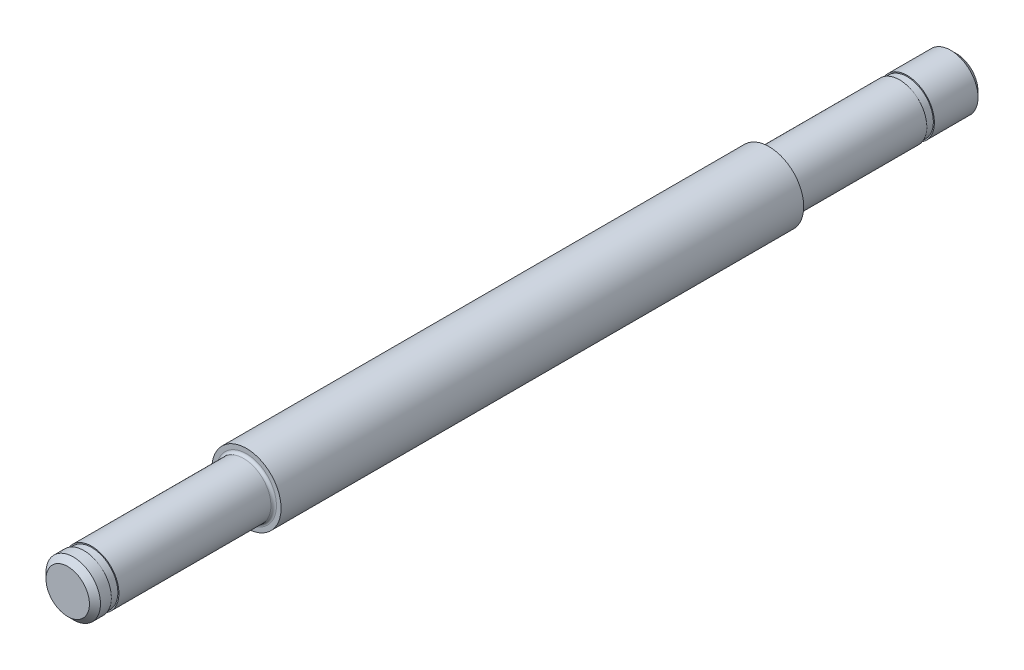
SolidWorks part; units mm, degrees
ref_plane "Front Plane" through (0, 0, 0) normal (0, 0, 1) x (1, 0, 0)
ref_plane "Top Plane" through (0, 0, 0) normal (0, 1, 0) x (1, 0, 0)
ref_plane "Right Plane" through (0, 0, 0) normal (1, 0, 0) x (0, 0, -1)
sketch "Sketch1" plane through (0, 0, 0) normal (0, 0, 1) x (1, 0, 0)
  circle A0 centre (0, 0) radius 2.5
  dimension "D1" = 5
extrude "Boss-Extrude1" add sketch "Sketch1" along normal mid plane 81.534
ref_axis "Axis1" through (0, 0, 40.767) along (0, 0, -1)
sketch "Sketch2" plane through (0, 0, 0) normal (1, 0, 0) x (0, 0, -1)
  line L0 (40.767, 2.5) -> (-40.767, 2.5) construction
  line L1 (-39.2646, 2.5) -> (-38.5646, 2.5)
  line L2 (-39.2646, 2.5) -> (-39.2646, 2.4)
  line L3 (-39.2646, 2.4) -> (-38.5646, 2.4)
  line L4 (-38.5646, 2.5) -> (-38.5646, 2.4)
  line L5 (-38.5646, -74.4231) -> (-38.5646, -68.0725) construction
  dimension "D1" = 0.1
  dimension "D2" = 0.7
revolve "Cut-Revolve1" cut sketch "Sketch2" angle 360 about axis through (0, 0, 40.767) along (0, 0, -1)
sketch "Sketch4" plane through (0, 0, -40.767) normal (0, 0, -1) x (-1, 0, 0)
  circle A0 centre (0, 0) radius 3.4022
extrude "Boss-Extrude2" [suppressed] add sketch "Sketch4" against normal up to surface (5.1753 mm away)
sketch "Sketch5" plane through (0, 0, 24.3646) normal (0, 0, -1) x (-1, 0, 0)
  circle A0 centre (0, 0) radius 3.175
  dimension "D1" = 6.35
extrude "Boss-Extrude3" add sketch "Sketch5" along normal blind 47.9552
ref_axis "Axis2" through (0, 0, -23.5906) along (0, 0, -1)
sketch "Sketch7" plane through (0, -92.7159, 0) normal (1, 0, 0) x (0, 0, 1)
  line L0 (-40.767, -95.2159) -> (-23.5906, -95.2159) construction
  line L1 (-36.262, -95.1159) -> (-35.562, -95.1159)
  line L2 (-36.262, -95.1159) -> (-36.262, -95.2159)
  line L3 (-36.262, -95.2159) -> (-35.562, -95.2159)
  line L4 (-35.562, -95.1159) -> (-35.562, -95.2159)
  dimension "D1" = 0.7
  dimension "D2" = 0.1
revolve "Cut-Revolve2" cut sketch "Sketch7" angle 360 about axis through (0, 0, -23.5906) along (0, 0, -1)
chamfer "Chamfer1" distance 0.508 angle 45 2 edges at (2.5, 0, 40.767) (2.5, 0, -40.767)
fillet "Fillet1" radius 0.254 2 edges at (-2.5, 0, -23.5906) (-2.5, 0, 24.3646)
